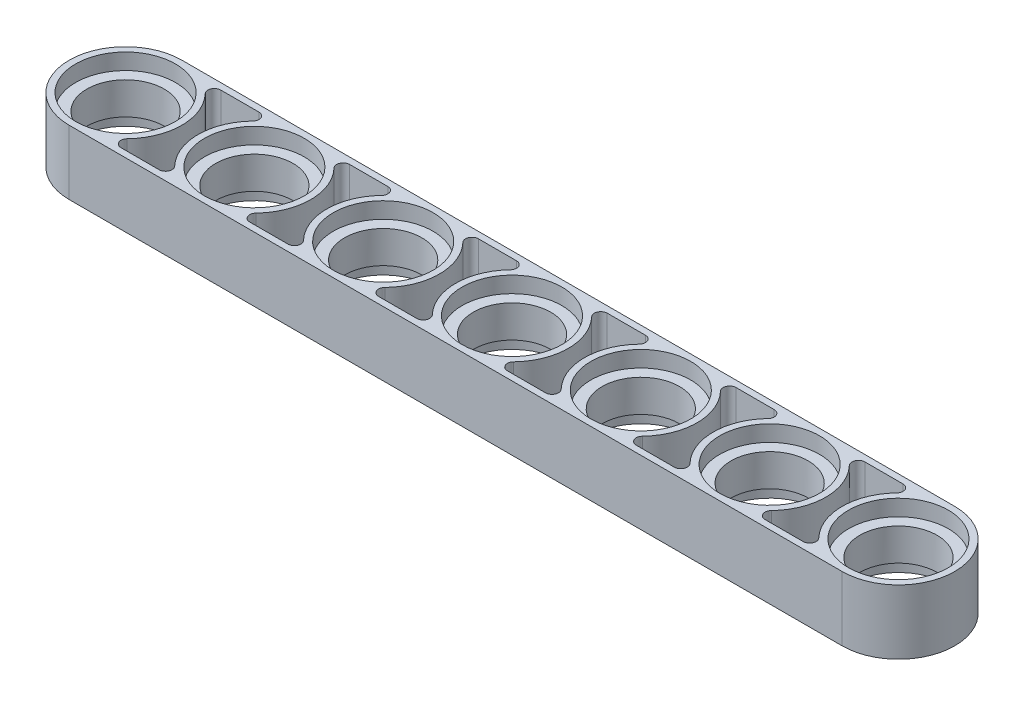
SolidWorks part; units mm, degrees
ref_plane "Front Plane" through (0, 0, 0) normal (0, 0, 1) x (1, 0, 0)
ref_plane "Top Plane" through (0, 0, 0) normal (0, 1, 0) x (1, 0, 0)
ref_plane "Right Plane" through (0, 0, 0) normal (1, 0, 0) x (0, 0, -1)
sketch "Sketch1" plane through (0, 0, 0) normal (0, 1, 0) x (1, 0, 0)
  line L0 (0, 0) -> (48, 0) construction
  line L1 (0, 3.5) -> (48, 3.5)
  line L2 (0, -3.5) -> (48, -3.5)
  arc A0 (0, 3.5) -> (0, -3.5) centre (0, 0) ccw
  arc A1 (48, -3.5) -> (48, 3.5) centre (48, 0) ccw
  point P3 (24, 0)
  point P8 (-3.5, 0)
  point P9 (51.5, 0)
  point P10 (0, 0)
  point P11 (0, 0)
  dimension "D1" = 55
  dimension "D2" = 7
extrude "Boss-Extrude1" add sketch "Sketch1" along normal mid plane 4
sketch "Sketch2" plane through (0, 2, 0) normal (0, 1, 0) x (1, 0, 0)
  circle A0 centre (0, 0) radius 3.1
  dimension "D1" = 6.2
extrude "Cut-Extrude1" cut sketch "Sketch2" against normal blind 1
sketch "Sketch3" plane through (0, -2, 0) normal (0, -1, 0) x (1, 0, 0)
  circle A0 centre (0, 0) radius 3.1
  dimension "D1" = 6.2
extrude "Cut-Extrude2" cut sketch "Sketch3" against normal blind 1
sketch "Sketch4" plane through (0, 1, 0) normal (0, 1, 0) x (1, 0, 0)
  circle A0 centre (0, 0) radius 2.4
  dimension "D1" = 4.8
extrude "Cut-Extrude3" cut sketch "Sketch4" against normal through all
pattern_linear "LPattern1" count 7 spacing 8 along (1, 0, 0) of "Cut-Extrude3", "Cut-Extrude2", "Cut-Extrude1"
sketch "Sketch5" plane through (0, 2, 0) normal (0, 1, 0) x (1, 0, 0)
  line L0 (2.8142, 3.1) -> (5.1858, 3.1)
  line L1 (2.8142, -3.1) -> (5.1858, -3.1)
  arc A0 (2.5256, -2.4231) -> (2.5256, 2.4231) centre (0, 0) ccw
  arc A1 (5.4744, 2.4231) -> (5.4744, -2.4231) centre (8, 0) ccw
  arc A6 (2.5256, -2.4231) -> (2.8142, -3.1) centre (2.8142, -2.7) ccw
  arc A7 (5.4744, -2.4231) -> (5.1858, -3.1) centre (5.1858, -2.7) cw
  arc A8 (5.1858, 3.1) -> (5.4744, 2.4231) centre (5.1858, 2.7) cw
  arc A9 (2.8142, 3.1) -> (2.5256, 2.4231) centre (2.8142, 2.7) ccw
  dimension "D1" = 7
  dimension "D2" = 7
  dimension "D3" = 0.4
extrude "Cut-Extrude4" cut sketch "Sketch5" against normal through all
pattern_linear "LPattern2" count 6 spacing 8 along (1, 0, 0) of "Cut-Extrude4"
